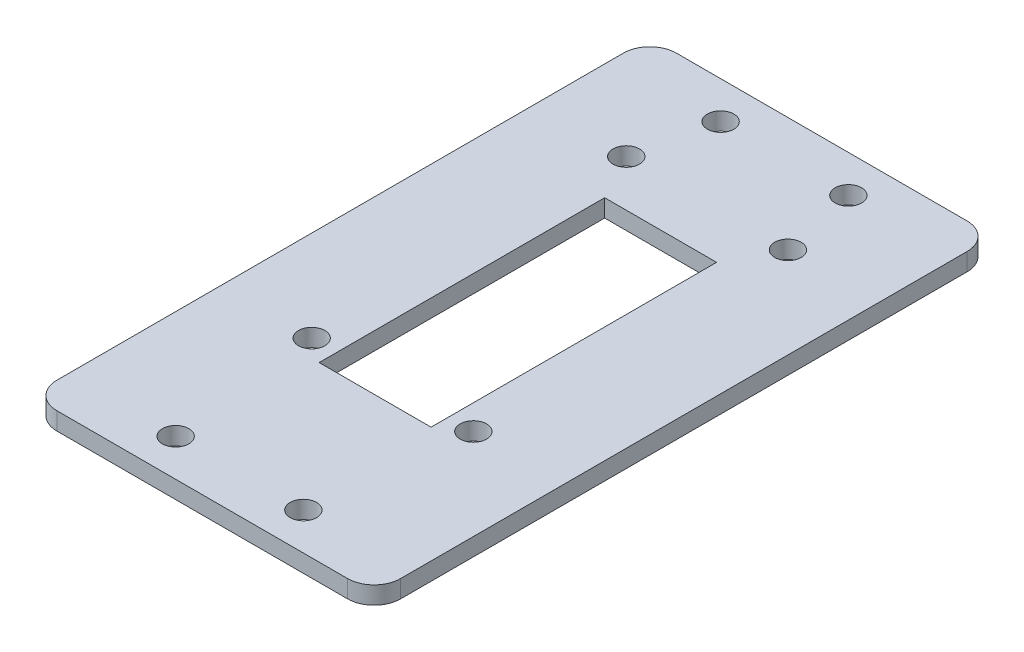
SolidWorks part; units mm, degrees
ref_plane "Front Plane" through (0, 0, 0) normal (0, 0, 1) x (1, 0, 0)
ref_plane "Top Plane" through (0, 0, 0) normal (0, 1, 0) x (1, 0, 0)
ref_plane "Right Plane" through (0, 0, 0) normal (1, 0, 0) x (0, 0, -1)
sketch "Sketch1" plane through (0, 0, 0) normal (0, 1, 0) x (1, 0, 0)
  line L0 (-5, -27.8904) -> (-10, -27.8904) construction
  line L1 (-10, -24.8904) -> (-5, -24.8904) construction
  line L2 (10, -27.8904) -> (5, -27.8904) construction
  line L3 (5, -24.8904) -> (10, -24.8904) construction
  line L8 (12, 29.5) -> (-12, 29.5)
  line L9 (12, -11.85) -> (12, 29.5)
  line L10 (-12, -11.85) -> (12, -11.85)
  line L11 (-12, 29.5) -> (-12, -11.85)
  line L12 (-5, 33.9596) -> (-9.5, 33.9596) construction
  line L13 (-9.5, 36.9596) -> (-5, 36.9596) construction
  line L14 (9.5, 33.9596) -> (5, 33.9596) construction
  line L15 (5, 36.9596) -> (9.5, 36.9596) construction
  line L16 (-5, -27.8904) -> (-10, -27.8904)
  line L17 (-10, -24.8904) -> (-5, -24.8904)
  line L18 (10, -27.8904) -> (5, -27.8904)
  line L19 (5, -24.8904) -> (10, -24.8904)
  line L20 (-5, 33.9596) -> (-9.5, 33.9596)
  line L21 (-9.5, 36.9596) -> (-5, 36.9596)
  line L22 (9.5, 33.9596) -> (5, 33.9596)
  line L23 (5, 36.9596) -> (9.5, 36.9596)
  line L24 (-9.75, 22.9156) -> (9.75, 22.9156) construction
  line L25 (10.25, 22.4156) -> (10.25, -17.5844) construction
  line L26 (9.75, -18.0844) -> (3.2887, -18.0844) construction
  line L27 (-10.25, -17.5844) -> (-10.25, 22.4156) construction
  line L28 (-9.75, 22.9156) -> (9.75, 22.9156)
  line L29 (10.25, 22.4156) -> (10.25, -17.5844)
  line L30 (9.75, -18.0844) -> (3.2887, -18.0844)
  line L31 (-10.25, -17.5844) -> (-10.25, 22.4156)
  arc A0 (-10, -24.8904) -> (-10, -27.8904) centre (-10, -26.3904) ccw construction
  circle A2 centre (-9.175, 26.675) radius 1.425
  circle A4 centre (-9.175, -9.025) radius 1.425
  circle A6 centre (9.175, -9.025) radius 1.425
  circle A8 centre (9.175, 26.675) radius 1.425
  arc A9 (-5, -27.8904) -> (-5, -24.8904) centre (-5, -26.3904) ccw construction
  arc A10 (5, -24.8904) -> (5, -27.8904) centre (5, -26.3904) ccw construction
  arc A11 (10, -27.8904) -> (10, -24.8904) centre (10, -26.3904) ccw construction
  arc A12 (-9.5, 36.9596) -> (-9.5, 33.9596) centre (-9.5, 35.4596) ccw construction
  arc A13 (-5, 33.9596) -> (-5, 36.9596) centre (-5, 35.4596) ccw construction
  arc A14 (5, 36.9596) -> (5, 33.9596) centre (5, 35.4596) ccw construction
  arc A15 (9.5, 33.9596) -> (9.5, 36.9596) centre (9.5, 35.4596) ccw construction
  arc A16 (-10, -24.8904) -> (-10, -27.8904) centre (-10, -26.3904) ccw
  arc A17 (-5, -27.8904) -> (-5, -24.8904) centre (-5, -26.3904) ccw
  arc A18 (5, -24.8904) -> (5, -27.8904) centre (5, -26.3904) ccw
  arc A19 (10, -27.8904) -> (10, -24.8904) centre (10, -26.3904) ccw
  arc A20 (-9.5, 36.9596) -> (-9.5, 33.9596) centre (-9.5, 35.4596) ccw
  arc A21 (-5, 33.9596) -> (-5, 36.9596) centre (-5, 35.4596) ccw
  arc A22 (5, 36.9596) -> (5, 33.9596) centre (5, 35.4596) ccw
  arc A23 (9.5, 33.9596) -> (9.5, 36.9596) centre (9.5, 35.4596) ccw
sketch "Sketch2" plane through (0, 0, 0) normal (0, 1, 0) x (1, 0, 0)
  line L0 (-9.5, 35.4596) -> (9.5, 35.4596) construction
  line L1 (-19.5, 39.6846) -> (19.5, 39.6846)
  line L2 (-19.5, 39.6846) -> (-19.5, -30.6154)
  line L3 (-19.5, -30.6154) -> (19.5, -30.6154)
  line L4 (19.5, 39.6846) -> (19.5, -30.6154)
  line L5 (-10, -26.3904) -> (10, -26.3904) construction
  line L6 (0, 35.4596) -> (0, -26.3904) construction
  circle A0 centre (-9.175, -9.025) radius 1.425 construction
  circle A1 centre (-9.175, 26.675) radius 1.425 construction
  circle A2 centre (9.175, -9.025) radius 1.425 construction
  circle A3 centre (9.175, 26.675) radius 1.425 construction
  circle A4 centre (-9.175, -9.025) radius 1.425
  circle A5 centre (-9.175, 26.675) radius 1.425
  circle A6 centre (9.175, -9.025) radius 1.425
  circle A7 centre (9.175, 26.675) radius 1.425
  point P16 (0, 39.6846)
  point P28 (19.5, 4.5346)
  point P29 (0, 4.5346)
  dimension "D1" = 39
  dimension "D2" = 70.3
sketch "Sketch3" plane through (0, 0, 0) normal (0, 1, 0) x (1, 0, 0)
  line L0 (-9.5, 35.4596) -> (-5, 35.4596) construction
  line L1 (5, 35.4596) -> (9.5, 35.4596) construction
  line L2 (5, 36.9596) -> (9.5, 36.9596) construction
  line L3 (-10, -26.3904) -> (10, -26.3904) construction
  line L4 (-6.15, -11) -> (6.15, -11) construction
  line L5 (6.15, 21.4) -> (-6.15, 21.4) construction
  line L6 (-6.15, -11) -> (6.15, -11) construction
  line L7 (6.15, 21.4) -> (-6.15, 21.4) construction
  line L8 (19.5, 39.6846) -> (-19.5, 39.6846)
  line L9 (19.5, -30.6154) -> (19.5, 39.6846)
  line L10 (-19.5, -30.6154) -> (19.5, -30.6154)
  line L11 (-19.5, 39.6846) -> (-19.5, -30.6154)
  line L12 (19.5, 39.6846) -> (-19.5, 39.6846)
  line L13 (19.5, -30.6154) -> (19.5, 39.6846)
  line L14 (-19.5, -30.6154) -> (19.5, -30.6154)
  line L15 (-19.5, 39.6846) -> (-19.5, -30.6154)
  line L16 (-6.35, 16.75) -> (-6.35, 0) construction
  line L17 (-6.35, 16.75) -> (-6.35, 0) construction
  line L18 (6.35, 0) -> (6.35, 16.75) construction
  line L19 (6.35, 0) -> (6.35, 16.75) construction
  line L21 (-6.35, 21.4) -> (6.35, 21.4)
  line L22 (-6.35, 21.4) -> (-6.35, -11)
  line L23 (-6.35, -11) -> (6.35, -11)
  line L24 (6.35, 21.4) -> (6.35, -11)
  circle A0 centre (-7.25, 35.4596) radius 1.5
  circle A1 centre (7.25, 35.4596) radius 1.5
  circle A2 centre (7.25, -26.3904) radius 1.5
  circle A3 centre (-7.25, -26.3904) radius 1.5
  circle A4 centre (-9.175, -9.025) radius 1.425 construction
  circle A5 centre (9.175, -9.025) radius 1.425 construction
  circle A6 centre (9.175, 26.675) radius 1.5
  circle A7 centre (-9.175, 26.675) radius 1.425 construction
  circle A8 centre (9.175, -9.025) radius 1.5
  circle A9 centre (9.175, 26.675) radius 1.425 construction
  circle A10 centre (-9.175, 26.675) radius 1.5
  circle A12 centre (-9.175, -9.025) radius 1.5
  dimension "D5" = 0
extrude "Boss-Extrude1" add sketch "Sketch3" against normal blind 2
fillet "Fillet1" radius 3 4 edges at (-19.5, -1, -39.6846) (19.5, -1, -39.6846) (-19.5, -1, 30.6154) (19.5, -1, 30.6154)
